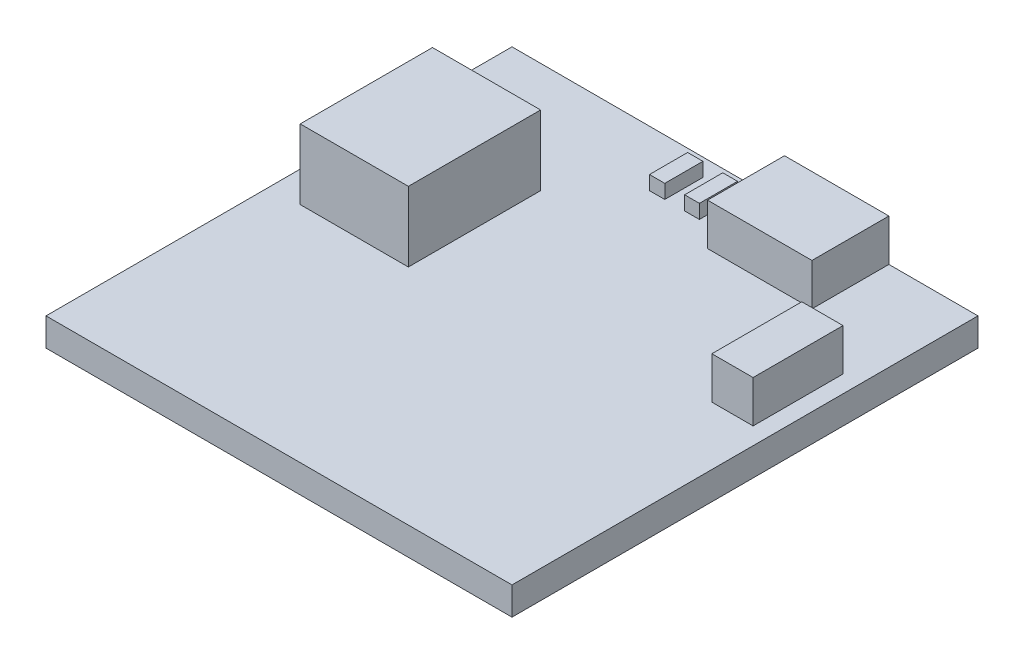
SolidWorks part; units mm, degrees
ref_plane "Front Plane" through (0, 0, 0) normal (0, 0, 1) x (1, 0, 0)
ref_plane "Top Plane" through (0, 0, 0) normal (0, 1, 0) x (1, 0, 0)
ref_plane "Right Plane" through (0, 0, 0) normal (1, 0, 0) x (0, 0, -1)
sketch "Sketch1" plane through (0, 0, 0) normal (0, 1, 0) x (1, 0, 0)
  line L1 (0, 0) -> (33.3375, 0)
  line L2 (0, 0) -> (0, 33.3375)
  line L3 (0, 33.3375) -> (33.3375, 33.3375)
  line L4 (33.3375, 0) -> (33.3375, 33.3375)
  dimension "D1" = 33.3375
  dimension "D2" = 33.3375
extrude "Boss-Extrude1" add sketch "Sketch1" along normal blind 2
sketch "Sketch2" plane through (0, 2, 0) normal (0, 1, 0) x (1, 0, 0)
  line L1 (2.1993, 25.4487) -> (9.9354, 25.4487)
  line L2 (2.1993, 25.4487) -> (2.1993, 15.9874)
  line L3 (2.1993, 15.9874) -> (9.9354, 15.9874)
  line L4 (9.9354, 25.4487) -> (9.9354, 15.9874)
extrude "Boss-Extrude2" add sketch "Sketch2" along normal blind 5
sketch "Sketch4" plane through (0, 2, 0) normal (0, 1, 0) x (1, 0, 0)
  line L1 (29.1642, 24.9078) -> (32.112, 24.9078)
  line L2 (29.1642, 24.9078) -> (29.1642, 18.4718)
  line L3 (29.1642, 18.4718) -> (32.112, 18.4718)
  line L4 (32.112, 24.9078) -> (32.112, 18.4718)
extrude "Boss-Extrude3" add sketch "Sketch4" along normal blind 3
sketch "Sketch5" plane through (0, 2, 0) normal (0, 1, 0) x (1, 0, 0)
  line L1 (13.8288, 32.073) -> (14.9222, 32.073)
  line L2 (13.8288, 32.073) -> (13.8288, 29.3435)
  line L3 (13.8288, 29.3435) -> (14.9222, 29.3435)
  line L4 (14.9222, 32.073) -> (14.9222, 29.3435)
  line L5 (16.3429, 32.073) -> (17.3999, 32.073)
  line L6 (16.3429, 32.073) -> (16.3429, 29.3435)
  line L7 (16.3429, 29.3435) -> (17.3999, 29.3435)
  line L8 (17.3999, 32.073) -> (17.3999, 29.3435)
extrude "Boss-Extrude4" add sketch "Sketch5" along normal blind 1
sketch "Sketch6" plane through (0, 2, 0) normal (0, 1, 0) x (1, 0, 0)
  line L0 (33.3375, 33.3375) -> (0, 33.3375) construction
  line L1 (19.4955, 27.8321) -> (26.9636, 27.8321)
  line L2 (19.4955, 27.8321) -> (19.4955, 33.3375)
  line L3 (19.4955, 33.3375) -> (26.9636, 33.3375)
  line L4 (26.9636, 27.8321) -> (26.9636, 33.3375)
extrude "Boss-Extrude5" add sketch "Sketch6" along normal blind 3
